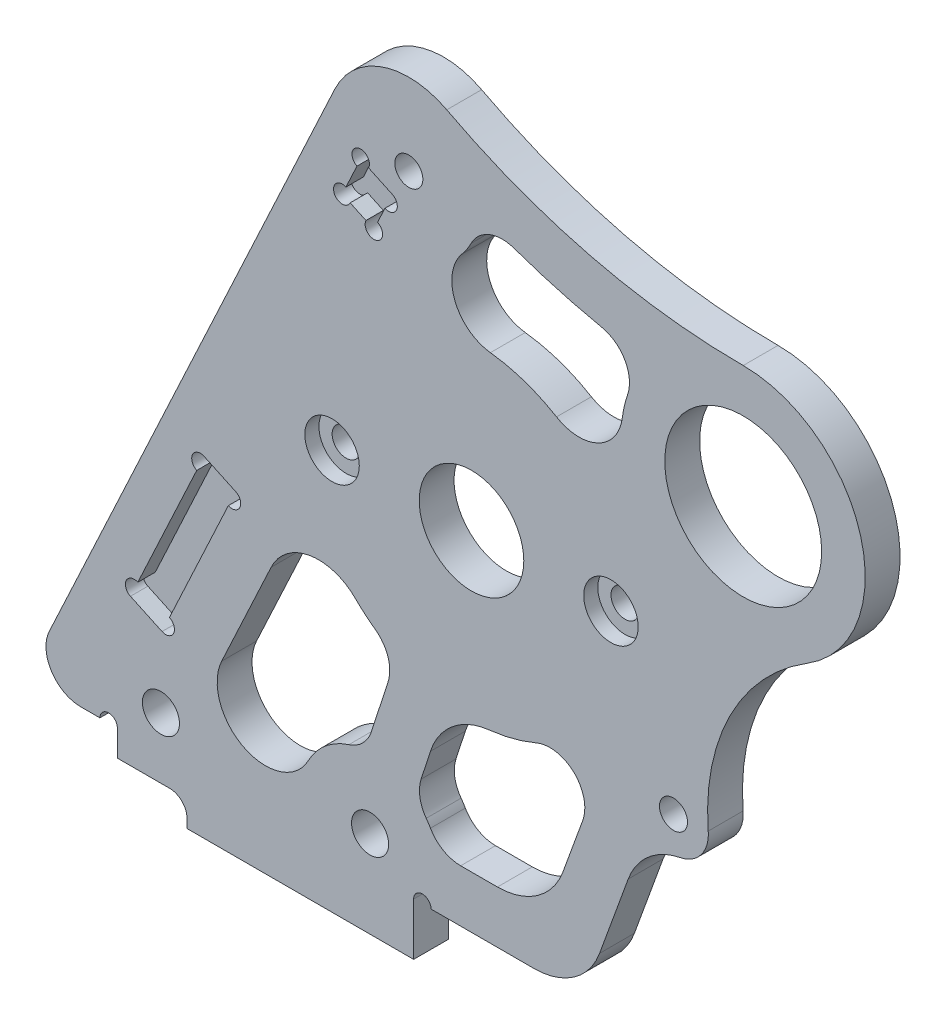
SolidWorks part; units mm, degrees
material "6061 Alloy"
ref_plane "Front" through (0, 0, 0) normal (0, 0, 1) x (1, 0, 0)
ref_plane "Top" through (0, 0, 0) normal (0, 1, 0) x (1, 0, 0)
ref_plane "Right" through (0, 0, 0) normal (1, 0, 0) x (0, 0, -1)
ref_plane "Plane1" through (0, -6.35, 0) normal (0, 1, 0) x (1, 0, 0)
sketch "Sketch1" plane through (0, 0, 0) normal (0, 0, 1) x (1, 0, 0)
  line L11 (-120.65, 0) -> (-117.1793, 0)
  line L13 (-74.3592, 120.6462) -> (-126.4051, 9.0336)
  line L14 (0, 91.95) -> (-105.7597, 30.8896) construction
  line L15 (0, -50) -> (0, 50) construction
  line L17 (-57.4569, 110.3295) -> (-63.6397, 117.5751) construction
  line L20 (-57.4569, 110.3295) -> (-49.8995, 101.4728) construction
  line L21 (-101.3043, -9.525) -> (-101.3043, -7.9375)
  line L22 (-104.4793, -4.7625) -> (-114.0043, -4.7625)
  line L23 (-60.0293, -2.3813) -> (-114.0043, -2.3813) construction
  line L24 (-20.946, 22.698) -> (-26.1659, 8.3563)
  line L25 (-17.5423, 40.5083) -> (-49.4934, 63.375) construction
  line L26 (-11.5385, 42.0703) -> (0, 91.95) construction
  line L29 (-114.0043, 0) -> (-114.0043, -4.7625)
  line L30 (-101.3043, -9.525) -> (-60.0293, -9.525)
  line L35 (-60.0293, 0) -> (-60.0293, -9.525)
  line L36 (-56.8543, 0) -> (-38.1, 0)
  line L37 (-127, 15.8461) -> (-127, -17.2126) construction
  circle A5 centre (0, 91.95) radius 2.55 construction
  arc A8 (11.6453, 73.0202) -> (0, 114.175) centre (0, 91.95) ccw
  arc A9 (11.6453, 73.0202) -> (-6.3713, 37.5473) centre (31.6087, 40.5691) ccw
  arc A10 (-26.1659, 8.3563) -> (-38.1, 0) centre (-38.1, 12.7) cw
  circle A13 centre (0, 91.95) radius 14.2875
  circle A14 centre (-49.4934, 63.375) radius 38.1 construction
  arc A16 (-120.65, 0) -> (-126.4051, 9.0336) centre (-120.65, 6.35) cw
  arc A18 (-53.9994, 127.5095) -> (-74.3592, 120.6462) centre (-60.9081, 114.3739) ccw
  arc A19 (0, 114.175) -> (-53.9994, 127.5095) centre (0, 230.1799) cw
  circle A20 centre (-49.4934, 63.375) radius 38.1 construction
  circle A21 centre (-49.4934, 63.375) radius 38.1 construction
  circle A22 centre (0, 91.95) radius 50.8 construction
  circle A23 centre (-57.4569, 110.3295) radius 4.7625 construction
  circle A24 centre (-57.4569, 110.3295) radius 9.525 construction
  circle A25 centre (-87.0168, 0) radius 33.6332 construction
  arc A26 (-114.0043, 0) -> (-117.1793, 0) centre (-115.5918, 0) ccw
  arc A29 (-56.8543, 0) -> (-60.0293, 0) centre (-58.4418, 0) ccw
  arc A30 (-101.3043, -7.9375) -> (-104.4793, -4.7625) centre (-104.4793, -7.9375) ccw
  arc A31 (-11.4715, 30.8139) -> (-6.3713, 37.5473) centre (-12.7013, 37.0437) ccw
  circle A32 centre (-12.7013, 37.0437) radius 4.7625 construction
  arc A33 (-11.4715, 30.8139) -> (-20.946, 22.698) centre (-9.0119, 18.3543) ccw
  circle A34 centre (-11.5385, 42.0703) radius 0.3969 construction
  circle A35 centre (-17.5423, 40.5083) radius 1.1906 construction
  point P35 (-53.3837, 0)
  point P46 (-87.0168, -2.3813)
  dimension "D1" = 22.225
  dimension "D2" = 53.975
  dimension "D5" = 76.2
  dimension "D6" = 12.7
  dimension "D7" = 127
  dimension "D8" = 28.575
  dimension "D11" = 19.05
  dimension "D13" = 101.6
  dimension "D14" = 38.1
  dimension "D15" = 9.525
  dimension "D17" = 1.5875
  dimension "D21" = 3.175
  dimension "D22" = 12.7
  dimension "D23" = 9.525
  dimension "D25" = 12.7
  dimension "D26" = 0.7937
  dimension "D27" = 2.3812
  dimension "D9" = 6.35
  dimension "D3" = 60
  dimension "D4" = 65
  dimension "D18" = 9.525
  dimension "D19" = 4.7625
  dimension "D20" = 12.7
  dimension "D24" = 70
extrude "Boss-Extrude1" add sketch "Sketch1" along normal blind 6.35
ref_plane "Plane2" through (0, 0, 6.35) normal (0, 0, 1) x (1, 0, 0)
hole_wizard "3/4 (0.75) Diameter Hole1" positions "Sketch4" profile "Sketch5" hole size "3/4" standard "ANSI Inch" end condition through all
sketch "Sketch4" plane through (0, 0, 6.35) normal (0, 0, 1) x (1, 0, 0)
  circle A0 centre (-49.4934, 63.375) radius 38.1 construction
  point P0 (-49.4934, 63.375)
sketch "Sketch5" plane through (-49.4934, 63.375, 6.35) normal (1, 0, 0) x (0, -1, 0)
  line L0 (0, 0) -> (0, 6.35)
  line L1 (0, 6.35) -> (9.525, 6.35)
  line L2 (9.525, 6.35) -> (9.525, 0)
  line L5 (9.525, 0) -> (0, 0)
  line L11 (0, -6.35) -> (0, 107.95) construction
  dimension "Thru Hole Dia." = 19.05
  dimension "Thru Hole Depth" = 6.35
hole_wizard "CBORE for #10 Button Head Cap Screw1" positions "Sketch6" profile "Sketch7" counterbore size "#10" standard "ANSI Inch" end condition through all
sketch "Sketch6" plane through (0, 0, 6.35) normal (0, 0, -1) x (-1, 0, 0)
  line L0 (24.0934, 63.375) -> (74.8934, 63.375) construction
  circle A0 centre (49.4934, 63.375) radius 25.4 construction
  point P0 (24.0934, 63.375)
  point P2 (74.8934, 63.375)
  dimension "D1" = 50.8
sketch "Sketch7" plane through (-24.0934, 63.375, 6.35) normal (1, 0, 0) x (0, -1, 0)
  line L0 (0, 0) -> (0, 6.35)
  line L1 (0, 6.35) -> (2.5527, 6.35)
  line L3 (2.5527, 6.35) -> (2.5527, 2.5654)
  line L4 (2.5527, 2.5654) -> (4.9606, 2.5654)
  line L5 (4.9606, 2.5654) -> (4.9606, 0)
  line L7 (4.9606, 0) -> (0, 0)
  line L11 (0, -6.35) -> (0, 107.95) construction
  dimension "Thru Hole Dia." = 5.1054
  dimension "Thru Hole Depth" = 6.35
  dimension "C'Bore Dia." = 9.9212
  dimension "C'Bore Depth" = 2.5654
hole_wizard "1/4 Clearance Hole1" positions "Sketch14" profile "Sketch15" hole size "1/4" standard "ANSI Inch" end condition through all
sketch "Sketch14" plane through (0, 0, 0) normal (0, 0, -1) x (-1, 0, 0)
  line L3 (56.8543, 0) -> (38.1, 0) construction
  line L9 (120.65, 0) -> (117.1793, 0) construction
  line L10 (67.9668, 6.35) -> (106.0668, 6.35) construction
  circle A0 centre (67.9668, 6.35) radius 6.35 construction
  circle A3 centre (106.0668, 6.35) radius 6.35 construction
  point P19 (67.9668, 6.35)
  point P66 (106.0668, 6.35)
  point P74 (87.0168, 6.35)
  dimension "D2" = 12.7
  dimension "D3" = 38.1
sketch "Sketch15" plane through (-67.9668, 6.35, 0) normal (1, 0, 0) x (0, 1, 0)
  line L0 (0, 0) -> (0, 6.35)
  line L1 (0, 6.35) -> (3.3782, 6.35)
  line L2 (3.3782, 6.35) -> (3.3782, 0)
  line L5 (3.3782, 0) -> (0, 0)
  line L11 (0, -6.35) -> (0, 107.95) construction
  dimension "Thru Hole Dia." = 6.7564
  dimension "Thru Hole Depth" = 6.35
hole_wizard "#10 Clearance Hole2" positions "Sketch18" profile "Sketch19" hole size "#10" standard "ANSI Inch" end condition through all
sketch "Sketch18" plane through (0, 0, 0) normal (0, 0, -1) x (-1, 0, 0)
  arc A0 (74.3592, 120.6462) -> (53.9994, 127.5095) centre (60.9081, 114.3739) ccw construction
  arc A3 (6.3713, 37.5473) -> (11.4715, 30.8139) centre (12.7013, 37.0437) ccw construction
  point P0 (60.9081, 114.3739)
  point P7 (12.7013, 37.0437)
sketch "Sketch19" plane through (-60.9081, 114.3739, 0) normal (1, 0, 0) x (0, 1, 0)
  line L0 (0, 0) -> (0, 6.35)
  line L1 (0, 6.35) -> (2.5527, 6.35)
  line L2 (2.5527, 6.35) -> (2.5527, 0)
  line L5 (2.5527, 0) -> (0, 0)
  line L11 (0, -6.35) -> (0, 107.95) construction
  dimension "Thru Hole Dia." = 5.1054
  dimension "Thru Hole Depth" = 6.35
sketch "Sketch20" plane through (0, 0, 6.35) normal (0, 0, -1) x (-1, 0, 0)
  line L1 (92.4433, 48.0577) -> (98.1984, 50.7413)
  line L2 (93.7851, 45.1802) -> (104.5196, 22.16)
  line L3 (105.8614, 19.2824) -> (111.6165, 21.9661)
  line L4 (99.5402, 47.8638) -> (110.2747, 24.8436)
  line L5 (70.3497, 110.4631) -> (72.3624, 106.1468)
  line L6 (71.5945, 104.0371) -> (68.717, 102.6953)
  line L7 (66.6073, 103.4631) -> (65.2655, 106.3407)
  line L8 (63.9237, 109.2182) -> (68.24, 111.2309)
  line L11 (74.3592, 120.6462) -> (126.4051, 9.0336) construction
  line L12 (67.2782, 102.0244) -> (49.4934, 63.375) construction
  arc A0 (111.6165, 21.9661) -> (110.2747, 24.8436) centre (110.9456, 23.4048) ccw
  arc A1 (104.5196, 22.16) -> (105.8614, 19.2824) centre (105.1905, 20.7212) ccw
  arc A2 (92.4433, 48.0577) -> (93.7851, 45.1802) centre (93.1142, 46.619) ccw
  arc A3 (99.5402, 47.8638) -> (98.1984, 50.7413) centre (98.8693, 49.3026) ccw
  circle A4 centre (106.0668, 6.35) radius 6.35 construction
  circle A5 centre (106.0668, 15.875) radius 3.175 construction
  circle A6 centre (49.4934, 63.375) radius 39.37 construction
  circle A7 centre (60.9081, 114.3739) radius 4.7625 construction
  arc A10 (63.9237, 109.2182) -> (65.2655, 106.3407) centre (64.5946, 107.7794) ccw
  arc A11 (66.6073, 103.4631) -> (68.717, 102.6953) centre (67.2782, 102.0244) ccw
  arc A12 (71.5945, 104.0371) -> (72.3624, 106.1468) centre (73.0333, 104.708) ccw
  arc A13 (70.3497, 110.4631) -> (68.24, 111.2309) centre (69.6788, 111.9018) ccw
  circle A16 centre (66.6146, 100.5822) radius 1.5875 construction
  dimension "D3" = 1.5875
  dimension "D4" = 6.35
  dimension "D5" = 12.7
  dimension "D6" = 7.9375
  dimension "D7" = 78.74
  dimension "D8" = 9.525
  dimension "D10" = 3.175
  dimension "D1" = 6.35
  dimension "D2" = 31.75
  dimension "D9" = 7.9375
extrude "Cut-Extrude2" cut sketch "Sketch20" against normal mid plane 6.35
sketch "Sketch21" plane through (0, 0, 0) normal (0, 0, -1) x (-1, 0, 0)
  line L0 (24.0934, 63.375) -> (74.8934, 63.375) construction
  line L1 (94.9957, 20.046) -> (85.9871, 39.3651)
  line L2 (93.7851, 45.1802) -> (104.5196, 22.16) construction
  line L3 (51.4691, 9.525) -> (44.7695, 9.525)
  line L4 (32.8354, 17.8813) -> (29.2319, 27.7817)
  line L5 (20.946, 22.698) -> (26.1659, 8.3563) construction
  line L6 (56.8543, 0) -> (38.1, 0) construction
  line L7 (67.9668, 6.35) -> (49.4934, 63.375) construction
  line L8 (58.6676, 19.6022) -> (56.9714, 24.8379)
  line L9 (67.729, 22.5376) -> (64.6903, 31.9176)
  line L10 (57.1202, 24.3788) -> (66.1815, 27.3143) construction
  arc A0 (79.2177, 12.2414) -> (71.8355, 18.4464) centre (67.9668, 6.35) ccw
  circle A1 centre (106.0668, 6.35) radius 12.7 construction
  circle A2 centre (74.8934, 63.375) radius 12.7 construction
  circle A3 centre (24.0934, 63.375) radius 12.7 construction
  arc A4 (46.0493, 93.1767) -> (34.0052, 89.0677) centre (49.4934, 63.375) ccw
  arc A5 (37.6961, 35.792) -> (46.2589, 33.5499) centre (49.4934, 63.375) ccw
  arc A6 (22.0369, 94.8352) -> (21.0528, 99.0726) centre (0, 91.95) ccw
  circle A7 centre (0, 91.95) radius 14.2875 construction
  arc A8 (0, 114.175) -> (-11.6453, 73.0202) centre (0, 91.95) ccw construction
  arc A9 (49.5614, 108.6692) -> (51.2035, 106.1817) centre (60.9081, 114.3739) ccw
  circle A10 centre (12.7013, 37.0437) radius 6.35 construction
  arc A11 (67.0212, 39.028) -> (70.6403, 42.0958) centre (49.4934, 63.375) ccw
  arc A12 (85.9871, 39.3651) -> (70.6403, 42.0958) centre (77.3545, 35.3396) ccw
  arc A13 (6.3713, 37.5473) -> (11.4715, 30.8139) centre (12.7013, 37.0437) ccw construction
  arc A16 (79.2177, 12.2414) -> (94.9957, 20.046) centre (87.0168, 16.3254) ccw
  arc A18 (64.6903, 31.9176) -> (67.0212, 39.028) centre (70.7312, 33.8746) cw
  arc A19 (37.6961, 35.792) -> (29.2319, 27.7817) centre (35.199, 29.9535) ccw
  arc A20 (46.0493, 93.1767) -> (51.2035, 106.1817) centre (45.1381, 101.0617) ccw
  arc A21 (22.0369, 94.8352) -> (34.0052, 89.0677) centre (29.9073, 95.8656) ccw
  arc A22 (25.7645, 107.3225) -> (41.7748, 111.805) centre (0, 230.1799) ccw
  arc A24 (49.5614, 108.6692) -> (41.7748, 111.805) centre (43.888, 105.8169) ccw
  arc A25 (21.0528, 99.0726) -> (25.7645, 107.3225) centre (27.0678, 101.1077) cw
  arc A26 (57.74, 13.8801) -> (56.9683, 12.7) centre (67.9668, 6.35) ccw
  arc A27 (67.729, 22.5376) -> (71.8355, 18.4464) centre (73.7699, 24.4946) ccw
  arc A28 (56.9714, 24.8379) -> (46.2589, 33.5499) centre (44.8896, 20.9239) ccw
  arc A29 (51.4691, 9.525) -> (56.9683, 12.7) centre (51.4691, 15.875) ccw
  arc A30 (58.6676, 19.6022) -> (57.74, 13.8801) centre (52.6267, 17.6452) cw
  arc A31 (44.7695, 9.525) -> (32.8354, 17.8813) centre (44.7695, 22.225) cw
  arc A32 (0, 114.175) -> (53.9994, 127.5095) centre (0, 230.1799) ccw construction
  point P56 (61.6509, 25.8465)
  point P74 (63.1524, 36.6649)
  point P79 (54.091, 33.7294)
  point P84 (59.8078, 16.0824)
  dimension "D1" = 60
  dimension "D2" = 25.4
  dimension "D7" = 12.7
  dimension "D8" = 15.875
  dimension "D9" = 9.525
  dimension "D10" = 6.35
  dimension "D11" = 12.7
  dimension "D12" = 9.525
  dimension "D13" = 6.35
  dimension "D14" = 12.7
  dimension "D15" = 6.35
  dimension "D16" = 12.7
  dimension "D3" = 9.525
  dimension "D4" = 9.525
  dimension "D5" = 9.525
  dimension "D6" = 9.525
extrude "Cut-Extrude3" cut sketch "Sketch21" against normal through all contours A31 A29 A26 A30 L8 A28 A5 A19 L4 | L9 A27 A0 A16 L1 A12 A11 A18 | A25 A6 A21 A4 A20 A9 A24 A22
